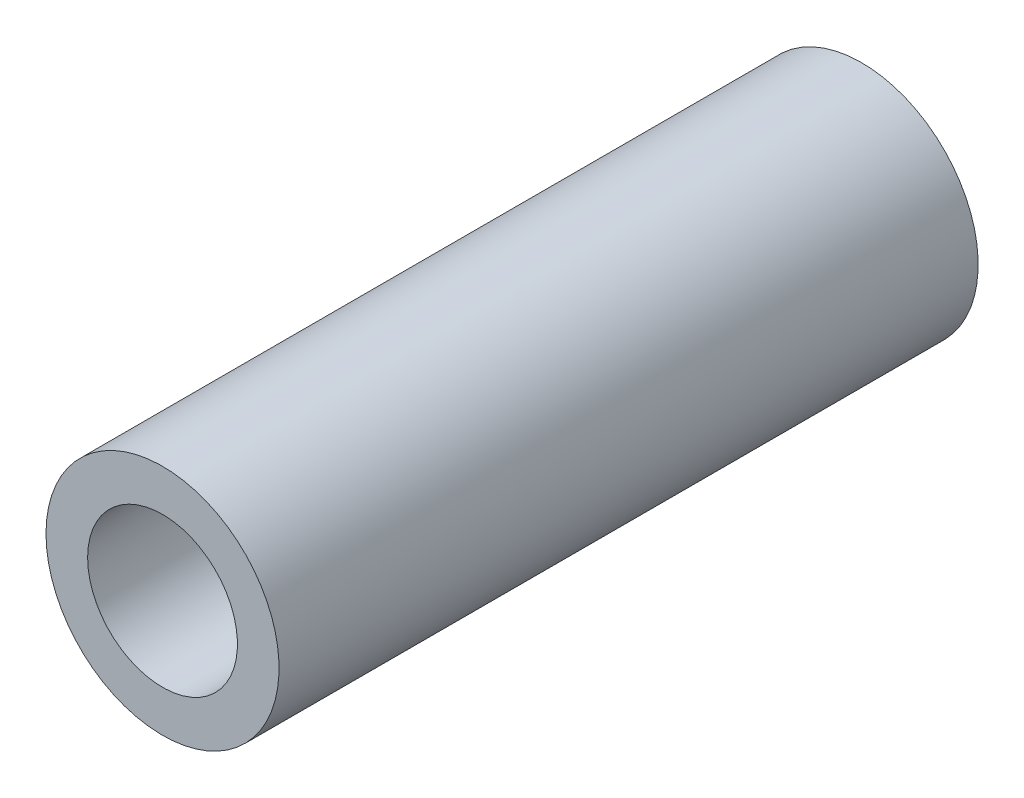
SolidWorks part; units mm, degrees
ref_plane "Front Plane" through (0, 0, 0) normal (0, 0, 1) x (1, 0, 0)
ref_plane "Top Plane" through (0, 0, 0) normal (0, 1, 0) x (1, 0, 0)
ref_plane "Right Plane" through (0, 0, 0) normal (1, 0, 0) x (0, 0, -1)
sketch "Sketch2" plane through (0, 0, 0) normal (0, 0, 1) x (1, 0, 0)
  circle A0 centre (0, 0) radius 2.25
  circle A1 centre (0, 0) radius 3.5
  dimension "D1" = 4.5
  dimension "D2" = 7
extrude "Boss-Extrude1" add sketch "Sketch2" along normal blind 21
